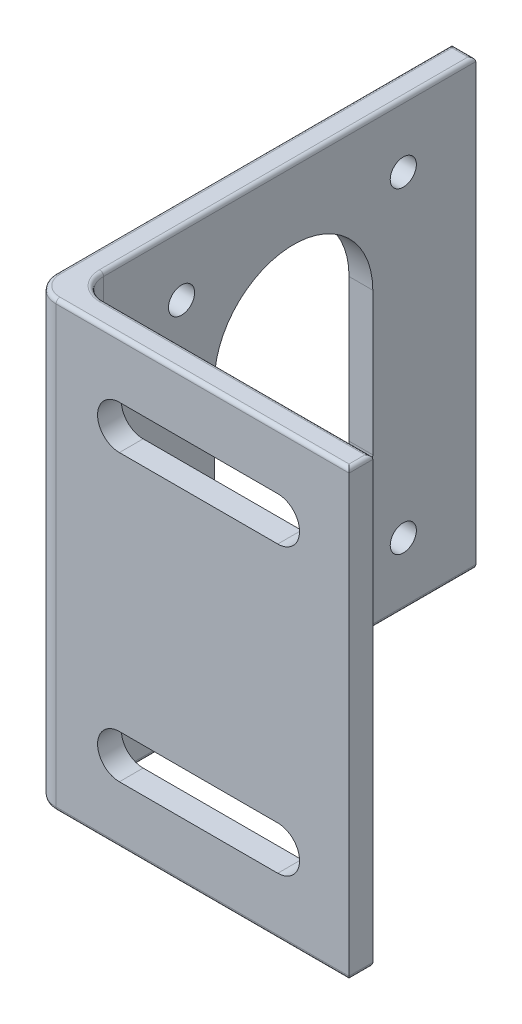
SolidWorks part; units mm, degrees
ref_plane "前视基准面" through (0, 0, 0) normal (0, 0, 1) x (1, 0, 0)
ref_plane "上视基准面" through (0, 0, 0) normal (0, 1, 0) x (1, 0, 0)
ref_plane "右视基准面" through (0, 0, 0) normal (1, 0, 0) x (0, 0, -1)
sketch "草图1" plane through (0, 0, 0) normal (0, 1, 0) x (1, 0, 0)
  line L2 (-18.5, 25) -> (-18.5, -25)
  line L3 (-18.5, -25) -> (18.5, -25)
  line L5 (-18.5, 25) -> (18.5, -25) construction
  line L6 (-18.5, -25) -> (0, 0) construction
  point P0 (0, 0)
  dimension "D1" = 50
  dimension "D2" = 37
extrude "拉伸-薄壁1" add sketch "草图1" along normal blind 56 thin
fillet "圆角1" radius 3 2 edges at (-18.5, 28, 25) (-21.5, 28, 28)
fillet "圆角2" radius 0.5 14 edges at (0, 0, 28) (18.5, 0, 26.5) (1.5, 0, 25) (-18.5, 0, -1.5) (-20, 0, -25) (-21.5, 0, 0) (18.5, 56, 26.5) (1.5, 56, 25) (-18.5, 56, -1.5) (-20, 56, -25) (-21.5, 56, 0) (0, 56, 28) (-20.6213, 0, 27.1213) (-20.6213, 56, 27.1213)
sketch "草图2" plane through (0, 0, 28) normal (0, 0, 1) x (1, 0, 0)
  line L0 (-21.5, 0.5) -> (-21.5, 55.5) construction
  line L1 (-10.5, 46) -> (9.5, 46)
  line L2 (-10.5, 46) -> (-10.5, 10)
  line L3 (-10.5, 10) -> (9.5, 10)
  line L4 (9.5, 46) -> (9.5, 10)
  line L5 (-10.5, 46) -> (9.5, 10) construction
  line L6 (-10.5, 10) -> (9.5, 46) construction
  line L7 (18.5, 28) -> (-18.5, 28) construction
  line L8 (18.5, 55.5) -> (18.5, 0.5) construction
  line L9 (-18.5, 55.5) -> (-18.5, 0.5) construction
  line L10 (-10.5, 46) -> (9.5, 46) construction
  line L11 (-10.5, 48.75) -> (9.5, 48.75)
  line L12 (-10.5, 43.25) -> (9.5, 43.25)
  line L13 (-10.5, 10) -> (9.5, 10) construction
  line L14 (-10.5, 7.25) -> (9.5, 7.25)
  line L15 (-10.5, 12.75) -> (9.5, 12.75)
  arc A0 (-10.5, 48.75) -> (-10.5, 43.25) centre (-10.5, 46) ccw
  arc A1 (9.5, 43.25) -> (9.5, 48.75) centre (9.5, 46) ccw
  arc A2 (-10.5, 7.25) -> (-10.5, 12.75) centre (-10.5, 10) cw
  arc A3 (9.5, 12.75) -> (9.5, 7.25) centre (9.5, 10) cw
  point P0 (-0.5, 28)
  point P13 (-0.5, 46)
  point P18 (-0.5, 10)
  dimension "D4" = 2.75
  dimension "D1" = 11
  dimension "D2" = 20
  dimension "D3" = 36
extrude "切除-拉伸1" cut sketch "草图2" against normal up to next contours L11 A1 L12 A0 | L14 A3 L15 A2
sketch "草图3" plane through (-21.5, 0, 0) normal (-1, 0, 0) x (0, 0, 1)
  line L0 (-2, 48) -> (-2, 8) construction
  line L1 (-16, 48) -> (12, 48)
  line L2 (-16, 48) -> (-16, 8)
  line L3 (-16, 8) -> (12, 8)
  line L4 (12, 48) -> (12, 8)
  line L5 (-16, 48) -> (12, 8) construction
  line L6 (-16, 8) -> (12, 48) construction
  line L7 (-25, 28) -> (28, 28) construction
  line L8 (-25, 55.5) -> (-25, 0.5) construction
  line L9 (28, 55.5) -> (28, 0.5) construction
  line L10 (-2, 19) -> (-2, 37) construction
  line L11 (-12, 19) -> (-12, 37)
  line L12 (8, 19) -> (8, 37)
  arc A0 (-12, 19) -> (8, 19) centre (-2, 19) ccw
  arc A1 (8, 37) -> (-12, 37) centre (-2, 37) ccw
  point P0 (-2, 28)
  point P14 (-2, 28)
  dimension "D4" = 10
  dimension "D5" = 18
  dimension "D1" = 28
  dimension "D2" = 40
  dimension "D3" = 30
extrude "切除-拉伸2" cut sketch "草图3" against normal up to next contours L12 A1 L11 A0
hole_wizard "M4 螺纹孔1" positions "3D草图2" profile "草图4" tap size "M4" standard "GB" end condition through all
sketch3d "3D草图2"
  line L0 (-21.5, 28, -25) -> (-21.5, 28, 25) construction
  line L1 (-21.5, 55.5, -25) -> (-21.5, 0.5, -25) construction
  line L2 (-21.5, 0.5, 25) -> (-21.5, 55.5, 25) construction
  line L15 (-21.5, 48, 12.1504) -> (-21.5, 8, 12.1504) construction
  line L16 (-21.5, 48, 12.1504) -> (-21.5, 48, -15.8496) construction
  line L17 (-21.5, 48, -15.8496) -> (-21.5, 8, -15.8496) construction
  line L18 (-21.5, 8, -15.8496) -> (-21.5, 8, 12.1504) construction
  line L19 (-21.5, 48, -15.8496) -> (-21.5, 8, 12.1504) construction
  line L20 (-21.5, 48, 12.1504) -> (-21.5, 8, -15.8496) construction
  line L22 (-18.5, 55.5, 28) -> (-18.5, 0.5, 28) construction
  point P15 (-21.5, 28, -1.8496)
  point P141 (-21.5, 48, -15.8496)
  point P142 (-21.5, 48, 12.1504)
  point P154 (-21.5, 48, 12.1504)
  point P156 (-21.5, 48, 12.1504)
  point P158 (-21.5, 48, 12.1504)
  point P160 (-21.5, 48, -15.8496)
  point P162 (-21.5, 8, 12.1504)
  point P164 (-21.5, 8, -15.8496)
  point P170 (-21.5, 48, -15.8496)
  point P184 (-21.5, 28, -1.8496)
  point P185 (-21.5, 28, -1.8496)
  dimension "D1" = 30
sketch "草图4" plane through (-21.5, 8, -15.8496) normal (0, 1, 0) x (0, 0, 1)
  line L0 (0, 0) -> (0, 40)
  line L1 (0, 40) -> (1.65, 40)
  line L2 (1.65, 40) -> (1.65, 0.6)
  line L3 (1.65, 0.6) -> (2.25, 0)
  line L5 (2.25, 0) -> (0, 0)
  line L6 (-1.65, 0.6) -> (-2.25, 0) construction
  line L11 (0, -6.35) -> (0, 107.95) construction
  dimension "通孔螺纹孔钻头直径" = 3.3
  dimension "通孔螺纹孔钻头深度" = 40
  dimension "近端锥形沉头孔直径" = 4.5
  dimension "近端锥形沉头孔角度" = 90
cosmetic thread "孔螺蚊线1" parameters "D2"=4
cosmetic thread "孔螺蚊线2" parameters "D2"=4
cosmetic thread "孔螺蚊线3" parameters "D2"=4
cosmetic thread "孔螺蚊线4" parameters "D2"=4
cosmetic thread "孔螺蚊线5" parameters "D2"=4
cosmetic thread "孔螺蚊线6" parameters "D2"=4
cosmetic thread "孔螺蚊线7" parameters "D2"=4
cosmetic thread "孔螺蚊线8" parameters "D2"=4
cosmetic thread "孔螺蚊线9" parameters "D2"=4
cosmetic thread "孔螺蚊线10" parameters "D2"=4
cosmetic thread "孔螺蚊线11" parameters "D2"=4
